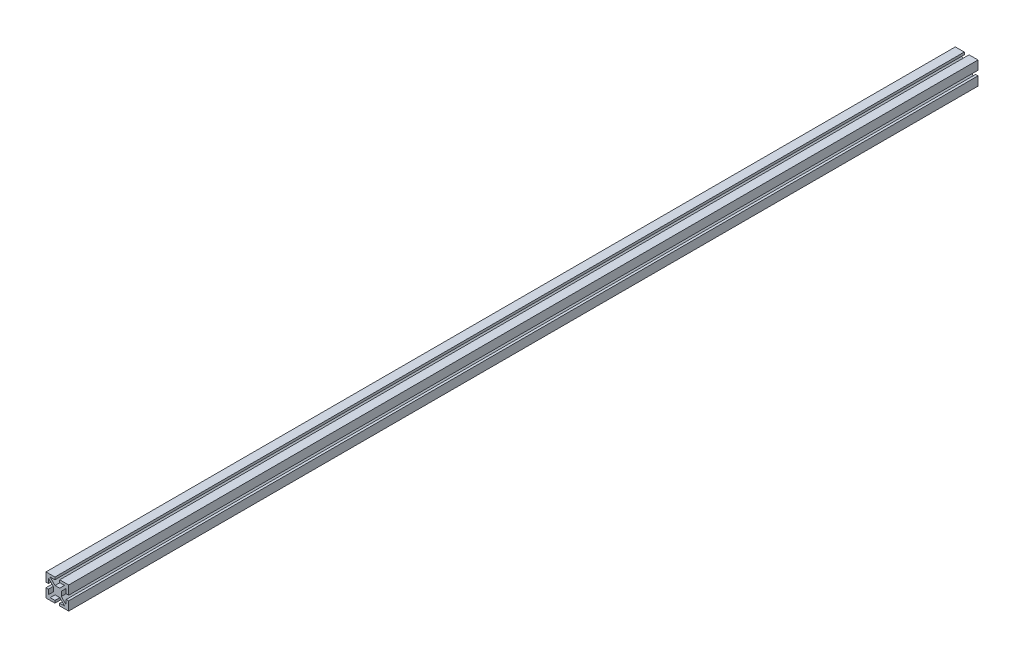
SolidWorks part; units mm, degrees
ref_plane "Front Plane" through (0, 0, 0) normal (0, 0, 1) x (1, 0, 0)
ref_plane "Top Plane" through (0, 0, 0) normal (0, 1, 0) x (1, 0, 0)
ref_plane "Right Plane" through (0, 0, 0) normal (1, 0, 0) x (0, 0, -1)
sketch "Sketch2" plane through (0.5947, -0.5947, 0) normal (0, 0, 1) x (1, 0, 0)
  line L0 (-0.5947, 0.5947) -> (-0.5947, 20.2394) construction
  line L1 (-0.5947, 0.5947) -> (-20.2394, 0.5947) construction
  line L2 (-0.5947, 0.5947) -> (-20.2394, 20.2394) construction
  line L3 (-19.6447, 19.6447) -> (-4.6587, 19.6447)
  line L4 (-4.6587, 19.6447) -> (-4.6587, 15.5807)
  line L5 (-4.6587, 15.5807) -> (-12.707, 15.5807)
  line L6 (-12.707, 15.5807) -> (-4.4774, 7.3511)
  line L7 (-4.4774, 7.3511) -> (3.288, 7.3511)
  line L8 (-19.6447, 19.6447) -> (-19.6447, 4.6587)
  line L9 (-19.6447, 4.6587) -> (-15.5807, 4.6587)
  line L10 (-15.5807, 4.6587) -> (-15.5807, 12.707)
  line L11 (-15.5807, 12.707) -> (-7.3511, 4.4774)
  line L12 (-7.3511, 4.4774) -> (-7.3511, -3.288)
  line L13 (-4.4774, -6.1617) -> (3.288, -6.1617)
  line L14 (-12.707, -14.3913) -> (-4.4774, -6.1617)
  line L15 (-4.6587, -14.3913) -> (-12.707, -14.3913)
  line L16 (-4.6587, -18.4553) -> (-4.6587, -14.3913)
  line L17 (-19.6447, -18.4553) -> (-4.6587, -18.4553)
  line L18 (-19.6447, -18.4553) -> (-19.6447, -3.4693)
  line L19 (-19.6447, -3.4693) -> (-15.5807, -3.4693)
  line L20 (-15.5807, -3.4693) -> (-15.5807, -11.5176)
  line L21 (-15.5807, -11.5176) -> (-7.3511, -3.288)
  line L22 (11.5176, 15.5807) -> (3.288, 7.3511)
  line L23 (3.4693, 15.5807) -> (11.5176, 15.5807)
  line L24 (3.4693, 19.6447) -> (3.4693, 15.5807)
  line L25 (18.4553, 19.6447) -> (3.4693, 19.6447)
  line L26 (18.4553, 19.6447) -> (18.4553, 4.6587)
  line L27 (18.4553, 4.6587) -> (14.3913, 4.6587)
  line L28 (14.3913, 4.6587) -> (14.3913, 12.707)
  line L29 (14.3913, 12.707) -> (6.1617, 4.4774)
  line L30 (6.1617, 4.4774) -> (6.1617, -3.288)
  line L31 (14.3913, -11.5176) -> (6.1617, -3.288)
  line L32 (14.3913, -3.4693) -> (14.3913, -11.5176)
  line L33 (18.4553, -3.4693) -> (14.3913, -3.4693)
  line L34 (18.4553, -18.4553) -> (18.4553, -3.4693)
  line L35 (18.4553, -18.4553) -> (3.4693, -18.4553)
  line L36 (3.4693, -18.4553) -> (3.4693, -14.3913)
  line L37 (3.4693, -14.3913) -> (11.5176, -14.3913)
  line L38 (11.5176, -14.3913) -> (3.288, -6.1617)
  point P26 (-7.3511, 0.5947)
  point P27 (-0.5947, 7.3511)
  point P44 (-0.5947, -6.1617)
  dimension "D1" = 38.1
  dimension "D2" = 8.128
  dimension "D3" = 13.5128
  dimension "D4" = 4.064
  dimension "D5" = 4.064
extrude "Boss-Extrude1" add sketch "Sketch2" along normal blind 1528.7625
other "1515<1>"
